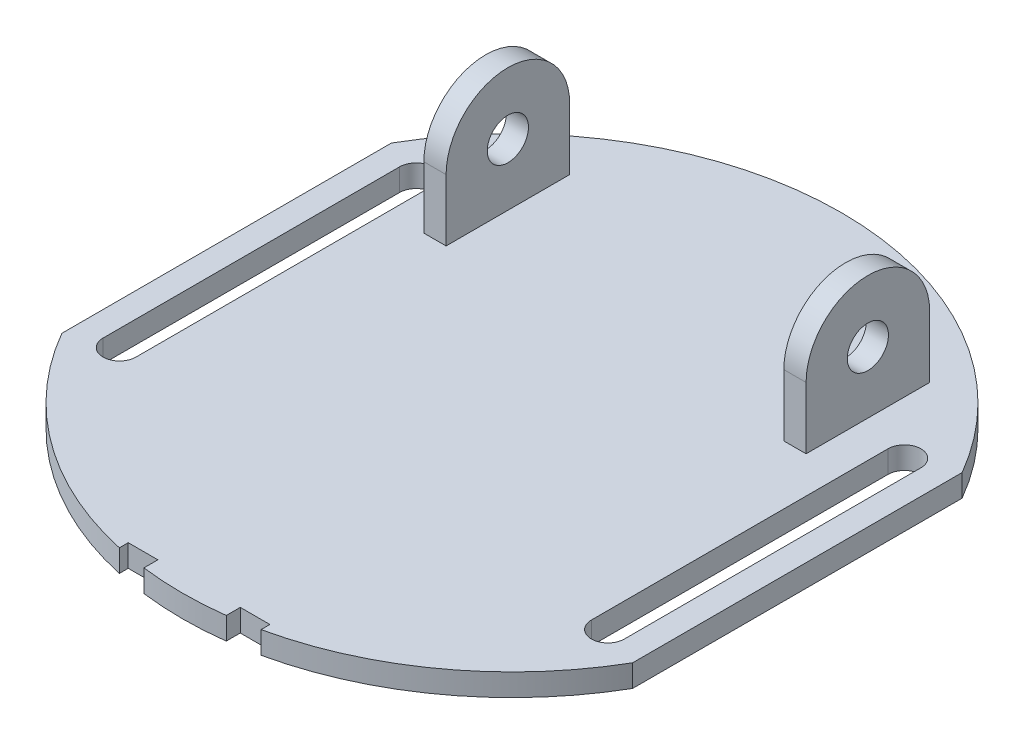
SolidWorks part; units mm, degrees
ref_plane "Front Plane" through (0, 0, 0) normal (0, 0, 1) x (1, 0, 0)
ref_plane "Top Plane" through (0, 0, 0) normal (0, 1, 0) x (1, 0, 0)
ref_plane "Right Plane" through (0, 0, 0) normal (1, 0, 0) x (0, 0, -1)
sketch "Sketch1" plane through (0, 0, 0) normal (0, 1, 0) x (1, 0, 0)
  line L0 (34.641, 20) -> (34.641, -20)
  line L1 (-34.641, 20) -> (-34.641, -20)
  line L2 (0, 40) -> (0, -40) construction
  arc A0 (-34.641, -20) -> (34.641, -20) centre (0, 0) ccw
  arc A1 (34.641, 20) -> (-34.641, 20) centre (0, 0) ccw
  dimension "D1" = 80
  dimension "D2" = 60
extrude "Base" add sketch "Sketch1" along normal blind 2.7
sketch "Sketch2" plane through (0, 2.7, 0) normal (0, 1, 0) x (-1, 0, 0)
  line L0 (29.641, -18) -> (29.641, 18) construction
  line L1 (27.641, -18) -> (27.641, 18)
  line L2 (31.641, -18) -> (31.641, 18)
  line L5 (34.641, -20) -> (34.641, 20) construction
  arc A0 (27.641, -18) -> (31.641, -18) centre (29.641, -18) ccw
  arc A1 (31.641, 18) -> (27.641, 18) centre (29.641, 18) ccw
  point P2 (29.641, 0)
  dimension "D1" = 2
  dimension "D2" = 2
  dimension "D3" = 4
  dimension "D4" = 5
extrude "Wheel Hole" cut sketch "Sketch2" against normal up to next
sketch "Sketch4" plane through (0, 2.7, 0) normal (0, 1, 0) x (-1, 0, 0)
  line L0 (34.641, -20) -> (-34.641, -20) construction
  line L1 (0, 40) -> (0, -40) construction
  arc A0 (-34.641, -20) -> (34.641, -20) centre (0, 0) ccw construction
  arc A1 (34.641, 20) -> (-34.641, 20) centre (0, 0) ccw construction
ref_plane "Battery Holder Ref Plane" through (-20.5, 0, 0) normal (1, 0, 0) x (0, 0, -1)
sketch "Sketch3" plane through (-20.5, 0, 0) normal (1, 0, 0) x (0, 0, -1)
  line L0 (27.5, 2.7) -> (27.5, 10.2)
  line L1 (40, 2.7) -> (20, 2.7) construction
  line L2 (12.5, 10.2) -> (12.5, 2.7)
  line L3 (20, 2.7) -> (-20, 2.7) construction
  line L4 (20, 17.7) -> (20, 2.7) construction
  line L5 (27.5, 2.7) -> (12.5, 2.7)
  arc A0 (27.5, 10.2) -> (12.5, 10.2) centre (20, 10.2) ccw
  circle A1 centre (20, 10.2) radius 2.5
  dimension "D1" = 7.5
  dimension "D3" = 5
  dimension "D2" = 7.5
extrude "Battery Holder" add sketch "Sketch3" against normal blind 2.7
sketch "Sketch5" plane through (0, 2.7, 0) normal (0, 1, 0) x (-1, 0, 0)
  line L0 (5, 39.6863) -> (5, 37.9863)
  line L1 (5, 37.9863) -> (8.6, 37.9863)
  line L2 (8.6, 37.9863) -> (8.6, 39.0646)
  line L3 (0, 40) -> (0, -40) construction
  arc A0 (34.641, 20) -> (-34.641, 20) centre (0, 0) ccw construction
  dimension "D1" = 3.6
  dimension "D2" = 1.7
  dimension "D3" = 5
extrude "IR Sensor Divot" cut sketch "Sketch5" against normal through all and the other way through all
mirror "Mirror" about plane through (0, 0, 0) normal (1, 0, 0) of "IR Sensor Divot", "Battery Holder", "Wheel Hole"
